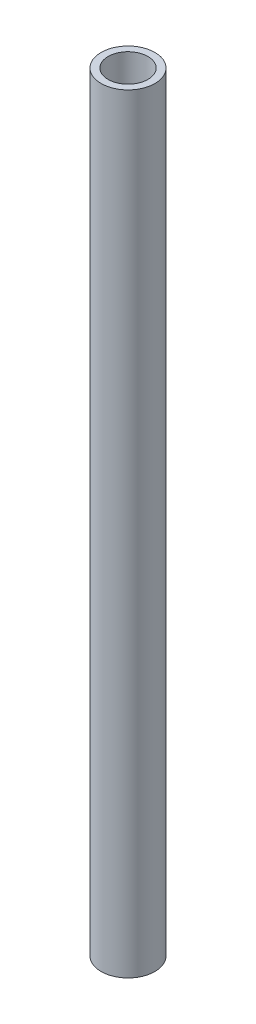
SolidWorks part; units mm, degrees
material "PVC Rigid"
ref_plane "Front Plane" through (0, 0, 0) normal (0, 0, 1) x (1, 0, 0)
ref_plane "Top Plane" through (0, 0, 0) normal (0, 1, 0) x (1, 0, 0)
ref_plane "Right Plane" through (0, 0, 0) normal (1, 0, 0) x (0, 0, -1)
sketch "Sketch1" plane through (0, 0, 0) normal (0, 1, 0) x (1, 0, 0)
  circle A0 centre (0, 0) radius 10.668
  circle A1 centre (0, 0) radius 7.8994
  dimension "D1" = 21.336
  dimension "D2" = 15.7988
extrude "Boss-Extrude1" add sketch "Sketch1" along normal blind 304.8
